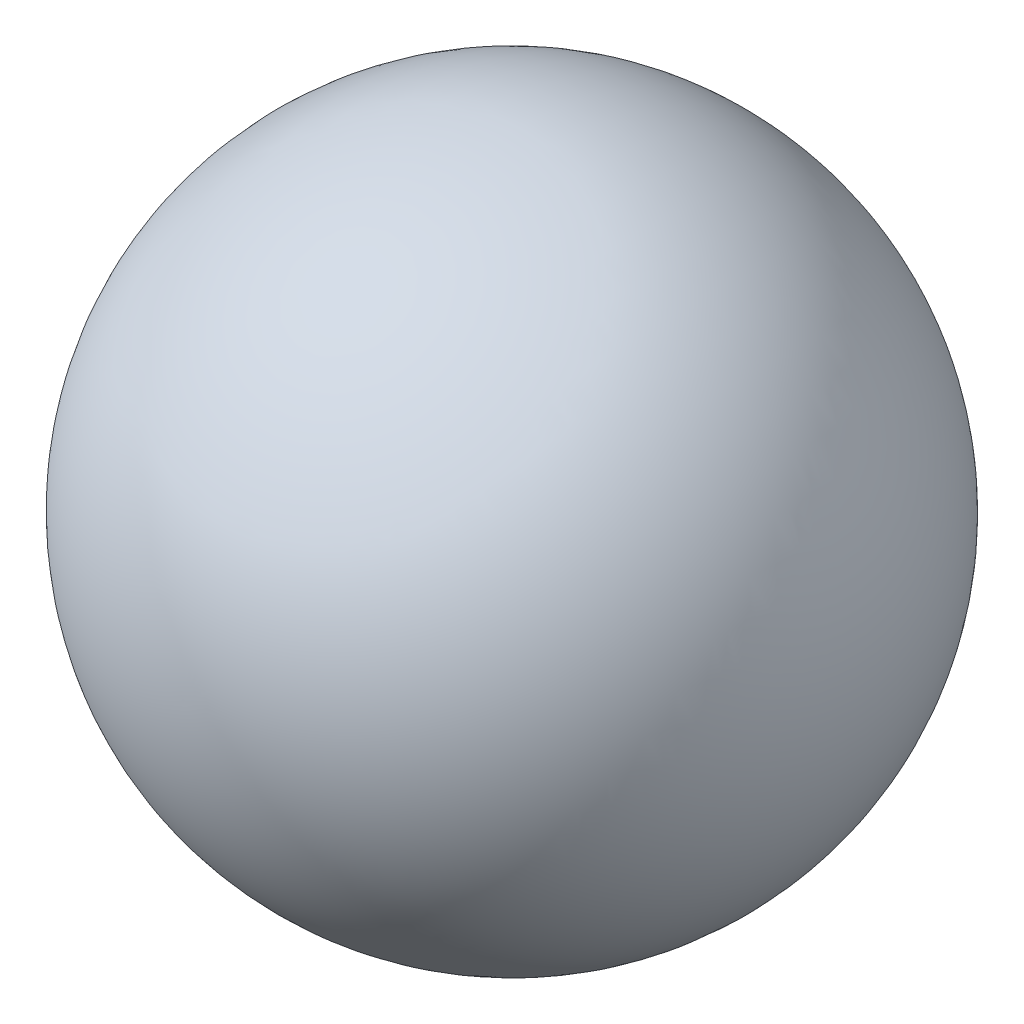
SolidWorks part; units mm, degrees
ref_plane "Front Plane" through (0, 0, 0) normal (0, 0, 1) x (1, 0, 0)
ref_plane "Top Plane" through (0, 0, 0) normal (0, 1, 0) x (1, 0, 0)
ref_plane "Right Plane" through (0, 0, 0) normal (1, 0, 0) x (0, 0, -1)
sketch "Sketch1" plane through (0, 0, 0) normal (0, 1, 0) x (1, 0, 0)
  line L0 (0.4988, 119.999) -> (0.4988, -119.999)
  arc A0 (0.4988, 119.999) -> (0.4988, -119.999) centre (0, 0) ccw
  dimension "D1" = 120
revolve "Revolve1" add sketch "Sketch1" angle 360 about L0
